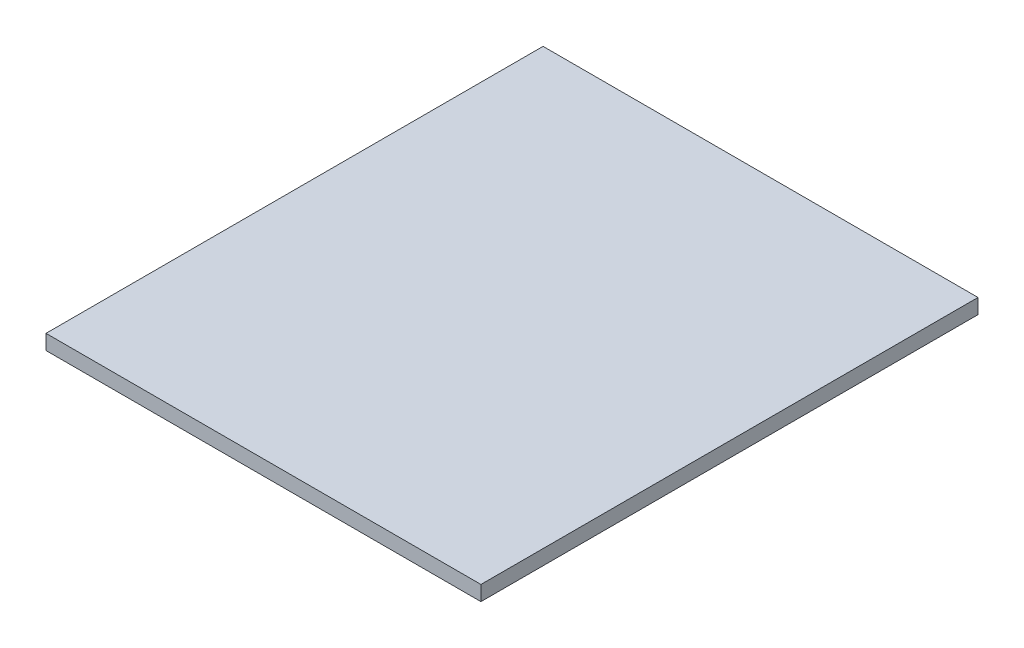
SolidWorks part; units mm, degrees
ref_plane "前视基准面" through (0, 0, 0) normal (0, 0, 1) x (1, 0, 0)
ref_plane "上视基准面" through (0, 0, 0) normal (0, 1, 0) x (1, 0, 0)
ref_plane "右视基准面" through (0, 0, 0) normal (1, 0, 0) x (0, 0, -1)
other "Configuration Table"
sketch "草图1" plane through (0, 0, 0) normal (0, 1, 0) x (1, 0, 0)
  line L1 (0, 0) -> (350, 0)
  line L2 (0, 0) -> (0, 400)
  line L3 (0, 400) -> (350, 400)
  line L4 (350, 0) -> (350, 400)
  dimension "D1" = 400
  dimension "D2" = 350
extrude "凸台-拉伸1" add sketch "草图1" along normal blind 12
